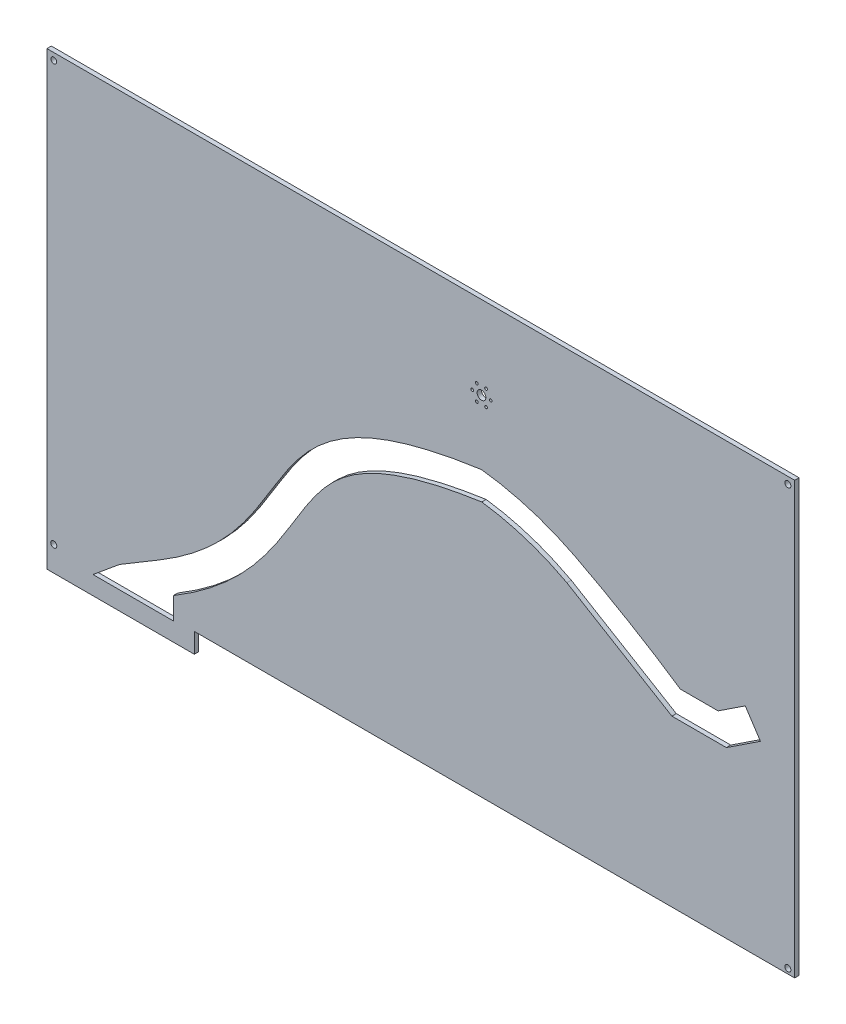
SolidWorks part; units mm, degrees
ref_plane "前视基准面" through (0, 0, 0) normal (0, 0, 1) x (1, 0, 0)
ref_plane "上视基准面" through (0, 0, 0) normal (0, 1, 0) x (1, 0, 0)
ref_plane "右视基准面" through (0, 0, 0) normal (1, 0, 0) x (0, 0, -1)
sketch "Sketch1" plane through (0, 0, 0) normal (0, 0, 1) x (1, 0, 0)
  line L0 (86.3892, 46.5642) -> (136.3892, 46.5642) construction
  line L1 (136.3892, 46.5642) -> (169.6686, 68.4983) construction
  line L2 (-475, -100) -> (-518.0311, -125.7444)
  line L3 (-436.8168, -147.9944) -> (-436.8168, -169.5504)
  line L4 (81.7745, 31.5642) -> (140.8878, 31.5642)
  line L5 (-467.2989, -112.8722) -> (-510.33, -138.6166) construction
  line L6 (140.8878, 31.5642) -> (177.9233, 55.9739)
  line L7 (-459.5978, -125.7444) -> (-459.5978, -149.5504)
  line L8 (-436.8168, -147.9944) -> (215.0808, -147.9944)
  line L9 (215.0808, -147.9944) -> (215.0808, 320)
  line L10 (215.0808, 320) -> (-596.8168, 320)
  line L11 (-596.8168, -150) -> (-596.8168, 320)
  line L12 (215.0808, -147.9944) -> (-596.8168, 320) construction
  line L13 (215.0808, 320) -> (-596.8168, -150) construction
  line L14 (-518.0311, -125.7444) -> (-459.5978, -125.7444) construction
  line L15 (-459.5978, -149.5504) -> (-546.7804, -149.5504)
  line L16 (-546.7804, -149.5504) -> (-518.0311, -125.7444)
  line L17 (90.9712, 61.5642) -> (131.8907, 61.5642)
  line L18 (-436.8168, -169.5504) -> (-596.8168, -169.5504)
  line L19 (-596.8168, -169.5504) -> (-596.8168, -150)
  line L21 (-32.3237, 100) -> (135.1953, 100) construction
  line L22 (-25, 130) -> (125, 130) construction
  line L23 (-28.6108, 115) -> (130.0228, 115) construction
  line L24 (131.8907, 61.5642) -> (161.4139, 81.0227)
  line L25 (177.9233, 55.9739) -> (161.4139, 81.0227)
  line L26 (-21.7014, 128.3139) -> (-25, 130)
  line L27 (-32.3237, 100) -> (81.7745, 31.5642)
  arc A0 (-125, 160) -> (-25, 130) centre (-159.8893, -137.9643) cw
  arc A1 (-28.6108, 115) -> (86.3892, 46.5642) centre (-559.3589, -907.7137) cw construction
  arc A2 (-124.7147, 129.7347) -> (-32.3237, 100) centre (-159.8893, -137.9643) cw
  circle A3 centre (-125, 230) radius 10 construction
  arc A4 (-124.84, 144.8723) -> (-28.6108, 115) centre (-159.8893, -137.9643) cw construction
  arc A5 (-21.7014, 128.3139) -> (90.9712, 61.5642) centre (-559.3589, -907.7137) cw
  circle A6 centre (-589.3757, -142.5578) radius 3.2924
  circle A7 centre (207.6422, -142.5578) radius 3.2924
  circle A8 centre (207.6422, 312.5578) radius 3.2944
  circle A9 centre (-589.3757, 312.5578) radius 3.1635
  arc A10 (135.1953, 100) -> (187.8618, 132.897) centre (303.6181, -111.0302) cw construction
  arc A11 (130.0228, 115) -> (181.4309, 146.4485) centre (303.6181, -111.0302) cw construction
  arc A12 (125, 130) -> (175, 160) centre (303.6181, -111.0302) cw construction
  arc A13 (-35.5202, 101.6861) -> (81.7745, 31.5642) centre (-559.3589, -907.7137) cw construction
  circle A14 centre (-135, 230) radius 1.5
  circle A15 centre (-130, 238.6603) radius 1.5
  circle A16 centre (-120, 238.6603) radius 1.5
  circle A17 centre (-115, 230) radius 1.5
  circle A18 centre (-120, 221.3397) radius 1.5
  circle A19 centre (-130, 221.3397) radius 1.5
  circle A20 centre (-125, 230) radius 4.7625
  spline S0 degree 3 poles (-475, -100) (-419.5406, -66.8201) (-329.5908, 43.116) (-307.6356, 134.2871) (-125, 160) knots 0 0 0 0 0.312224 1 1 1 1
  spline S1 degree 1 poles (-459.5978, -125.7444) (-124.7147, 129.7347) knots 0 0 1 1 construction
  spline S2 degree 3 poles (-459.5978, -125.7444) (-458.1292, -124.8657) (-455.1858, -123.0815) (-449.4714, -119.5247) (-442.5555, -115.0462) (-434.6362, -109.6397) (-424.5564, -102.3861) (-412.8294, -93.2453) (-400.0558, -82.1905) (-388.4865, -71.0922) (-374.5374, -56.3046) (-359.6201, -37.9792) (-344.8908, -16.7676) (-332.3401, 3.2457) (-321.0552, 21.7964) (-310.226, 38.6648) (-299.0796, 53.8348) (-286.8128, 67.5146) (-272.4318, 80.0885) (-257.6527, 89.9241) (-243.4982, 97.442) (-231.5651, 102.8866) (-218.1727, 108.1127) (-203.191, 113.0878) (-189.2817, 116.9961) (-177.2434, 119.9629) (-167.7458, 122.1041) (-157.766, 124.1573) (-149.0369, 125.7919) (-141.7993, 127.0518) (-136.2431, 127.9723) (-131.5022, 128.7191) (-127.6487, 129.3032) (-125.6903, 129.5925) (-124.7147, 129.7347) knots 0 0 0 0 0.007773 0.015545 0.03109 0.046636 0.062181 0.093271 0.124361 0.155452 0.186542 0.248723 0.310904 0.373084 0.435265 0.497446 0.559626 0.621807 0.683988 0.746169 0.777259 0.808349 0.83944 0.87053 0.90162 0.917166 0.932711 0.948256 0.963801 0.971574 0.979346 0.987119 0.991005 0.994892 0.994892 0.994892 0.994892
  spline S3 degree 1 poles (-467.2989, -112.8722) (-124.84, 144.8723) knots 0 0 1 1 construction
  spline S4 degree 3 poles (-467.2989, -112.8722) (-465.8766, -112.0213) (-463.025, -110.2926) (-457.4973, -106.8516) (-450.8174, -102.5249) (-443.1848, -97.3122) (-433.4896, -90.3317) (-422.2436, -81.559) (-410.0336, -70.981) (-398.9994, -60.3828) (-385.707, -46.2708) (-371.4731, -28.7597) (-357.2741, -8.2881) (-344.9599, 11.3612) (-333.6257, 29.9919) (-322.417, 47.4318) (-310.4985, 63.6121) (-297.0179, 78.5777) (-281.0248, 92.4603) (-264.7088, 103.2127) (-249.3105, 111.3089) (-236.4572, 117.1105) (-222.1723, 122.621) (-206.3349, 127.8161) (-191.7467, 131.8615) (-179.1859, 134.915) (-169.3063, 137.1107) (-158.9544, 139.2089) (-149.9221, 140.8739) (-142.4479, 142.1541) (-136.7117, 143.0887) (-130.8627, 143.9946) (-126.8382, 144.5862) (-124.84, 144.8723) knots 0 0 0 0 0.007793 0.015586 0.031173 0.046759 0.062345 0.093518 0.12469 0.155863 0.187036 0.249381 0.311726 0.374071 0.436417 0.498762 0.561107 0.623452 0.685798 0.748143 0.779315 0.810488 0.841661 0.872833 0.904006 0.919592 0.935179 0.950765 0.966351 0.974144 0.981937 0.989731 0.997524 0.997524 0.997524 0.997524 construction
  point P38 (-190, 85.5025)
  point P62 (-125, 230)
  dimension "D5" = 300
  dimension "D8" = 15
  dimension "D14" = 470
  dimension "D22" = 651.8975
  dimension "D23" = 70
  dimension "D24" = 100
  dimension "D26" = 6
  dimension "D27" = 3
  dimension "D28" = 9.525
  dimension "D29" = 20
  dimension "D1" = 105
  dimension "D2" = 100
  dimension "D3" = 350
  dimension "D4" = 260
  dimension "D6" = 100
  dimension "D7" = 30
  dimension "D9" = 15
  dimension "D10" = 115
  dimension "D11" = 50
  dimension "D13" = 15
  dimension "D15" = 190
  dimension "D16" = 320
  dimension "D17" = 20
  dimension "D25" = 811.9
  dimension "D12" = 30
extrude "Boss-Extrude1" add sketch "Sketch1" along normal blind 4.7625
